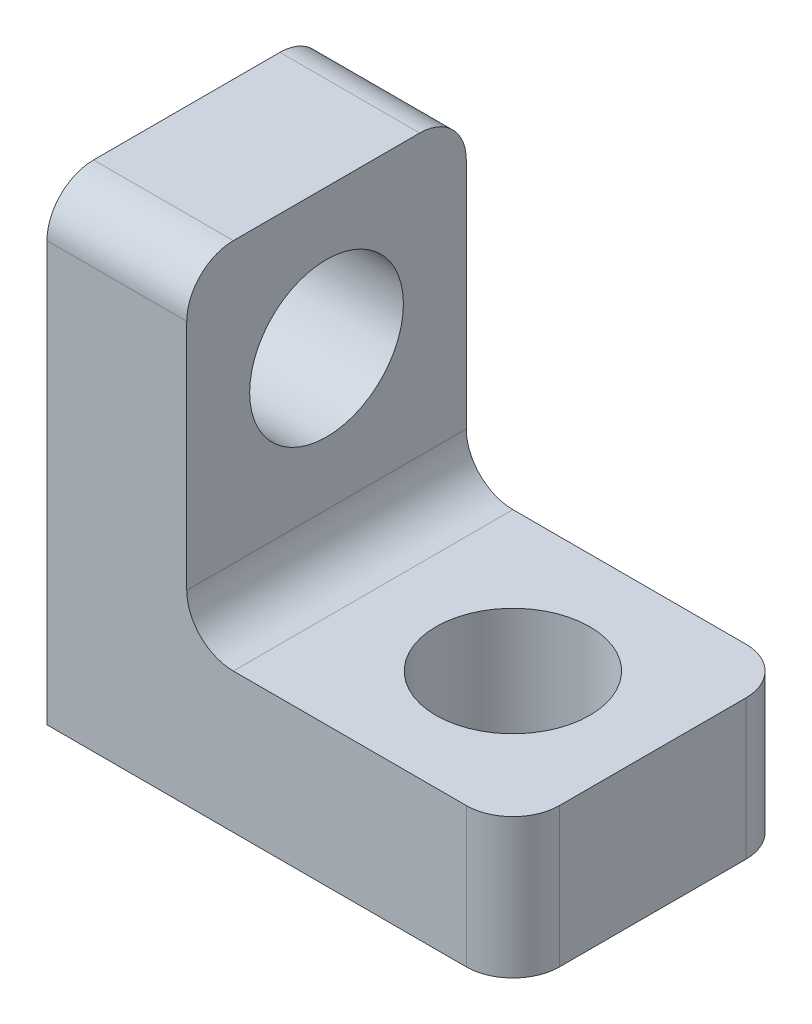
SolidWorks part; units mm, degrees
material "ABS"
ref_plane "前视基准面" through (0, 0, 0) normal (0, 0, 1) x (1, 0, 0)
ref_plane "上视基准面" through (0, 0, 0) normal (0, 1, 0) x (1, 0, 0)
ref_plane "右视基准面" through (0, 0, 0) normal (1, 0, 0) x (0, 0, -1)
sketch "草图1" plane through (0, 0, 0) normal (0, 0, 1) x (1, 0, 0)
  line L0 (10, 0) -> (0, 0)
  line L1 (0, 0) -> (0, 10)
  line L2 (0, 10) -> (3, 10)
  line L3 (3, 10) -> (3, 3)
  line L4 (3, 3) -> (10, 3)
  line L5 (10, 3) -> (10, 0)
  dimension "D1" = 10
  dimension "D2" = 3
extrude "凸台-拉伸1" add sketch "草图1" along normal blind 6
sketch "草图2" plane through (3, 0, 0) normal (1, 0, 0) x (0, 0, -1)
  line L0 (-6, 3) -> (-6, 10) construction
  line L1 (-6, 10) -> (0, 10) construction
  circle A0 centre (-3, 7) radius 1.65
  dimension "D1" = 3.3
  dimension "D2" = 3
  dimension "D3" = 3
extrude "切除-拉伸1" cut sketch "草图2" against normal blind 6
sketch "草图3" plane through (0, 3, 0) normal (0, 1, 0) x (1, 0, 0)
  line L0 (10, -6) -> (3, -6) construction
  line L1 (10, -6) -> (10, 0) construction
  circle A0 centre (7, -3) radius 1.65
  dimension "D1" = 3.3
  dimension "D2" = 3
  dimension "D3" = 3
extrude "切除-拉伸2" cut sketch "草图3" against normal blind 6
fillet "圆角1" radius 1 5 edges at (10, 1.5, 0) (10, 1.5, 6) (1.5, 10, 0) (1.5, 10, 6) (3, 3, 3)
